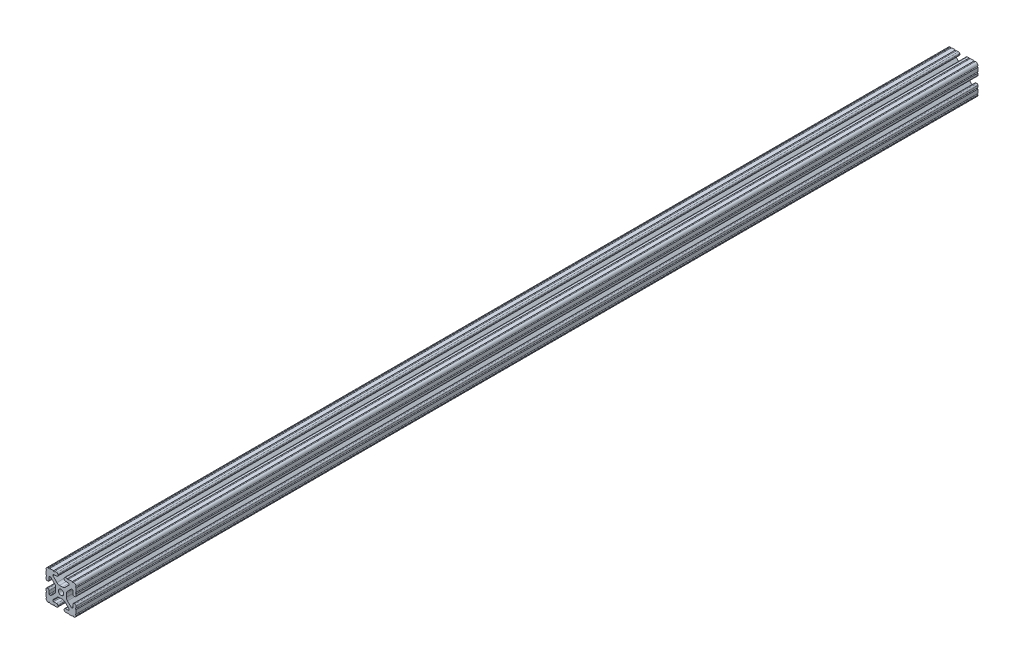
SolidWorks part; units mm, degrees
material "6061 Alloy"
ref_plane "Front Plane" through (0, 0, 0) normal (0, 0, 1) x (1, 0, 0)
ref_plane "Top Plane" through (0, 0, 0) normal (0, 1, 0) x (1, 0, 0)
ref_plane "Right Plane" through (0, 0, 0) normal (1, 0, 0) x (0, 0, -1)
sketch "Sketch1" plane through (0, 0, 0) normal (0, 0, 1) x (1, 0, 0)
  line L0 (0, 25.6181) -> (0, -24.623) construction
  line L1 (-20.8943, 0) -> (20.4607, 0) construction
  line L2 (-10.0229, 12.9148) -> (-5.2522, 8.144)
  line L3 (-10.287, 14.0843) -> (-10.287, 13.5524)
  line L4 (-5.6176, 14.986) -> (-9.3853, 14.986)
  line L5 (-4.064, 17.4964) -> (-4.064, 16.5396)
  line L6 (-7.9742, 19.05) -> (-5.6176, 19.05)
  line L7 (-14.3277, 19.05) -> (-9.4982, 19.05)
  line L8 (-19.05, 9.4961) -> (-19.05, 14.3277)
  line L9 (-19.05, 5.6176) -> (-19.05, 7.9763)
  line L10 (-16.5396, 4.064) -> (-17.4964, 4.064)
  line L11 (-14.986, 9.3853) -> (-14.986, 5.6176)
  line L12 (-13.516, 10.287) -> (-14.0843, 10.287)
  line L13 (-8.1476, 5.2921) -> (-12.8784, 10.0229)
  line L14 (-6.7564, -1.9335) -> (-6.7564, 1.9335)
  line L15 (-12.8784, -10.0229) -> (-8.1476, -5.2921)
  line L16 (-14.0843, -10.287) -> (-13.516, -10.287)
  line L17 (-14.986, -5.6176) -> (-14.986, -9.3853)
  line L18 (-17.4964, -4.064) -> (-16.5396, -4.064)
  line L19 (-19.05, -7.9763) -> (-19.05, -5.6176)
  line L20 (-19.05, -14.3277) -> (-19.05, -9.4961)
  line L21 (-9.4961, -19.05) -> (-14.3277, -19.05)
  line L22 (-5.6176, -19.05) -> (-7.9763, -19.05)
  line L23 (-4.064, -17.4964) -> (-4.064, -16.5396)
  line L24 (10.0229, -12.9148) -> (5.2522, -8.144)
  line L25 (10.287, -14.0843) -> (10.287, -13.5524)
  line L26 (5.6176, -14.986) -> (9.3853, -14.986)
  line L28 (-1.9022, 6.7564) -> (1.9022, 6.7564)
  line L29 (-1.9022, -6.7564) -> (1.9022, -6.7564)
  line L31 (-5.6176, -14.986) -> (-9.3853, -14.986)
  line L32 (-10.287, -14.0843) -> (-10.287, -13.5524)
  line L33 (-10.0229, -12.9148) -> (-5.2522, -8.144)
  line L66 (4.064, -16.5396) -> (4.064, -17.4964)
  line L67 (5.6176, -19.05) -> (7.9763, -19.05)
  line L68 (9.4961, -19.05) -> (14.3277, -19.05)
  line L69 (19.05, -14.3277) -> (19.05, -9.4961)
  line L70 (19.05, -7.9763) -> (19.05, -5.6176)
  line L71 (17.4964, -4.064) -> (16.5396, -4.064)
  line L72 (14.986, -5.6176) -> (14.986, -9.3853)
  line L73 (14.0843, -10.287) -> (13.516, -10.287)
  line L74 (12.8784, -10.0229) -> (8.1476, -5.2921)
  line L75 (6.7564, -1.9335) -> (6.7564, 1.9335)
  line L76 (8.1476, 5.2921) -> (12.8784, 10.0229)
  line L77 (13.516, 10.287) -> (14.0843, 10.287)
  line L78 (14.986, 9.3853) -> (14.986, 5.6176)
  line L79 (16.5396, 4.064) -> (17.4964, 4.064)
  line L80 (19.05, 5.6176) -> (19.05, 7.9763)
  line L81 (19.05, 9.4961) -> (19.05, 14.3277)
  line L82 (14.3277, 19.05) -> (9.4982, 19.05)
  line L83 (7.9742, 19.05) -> (5.6176, 19.05)
  line L84 (4.064, 17.4964) -> (4.064, 16.5396)
  line L85 (5.6176, 14.986) -> (9.3853, 14.986)
  line L86 (10.287, 14.0843) -> (10.287, 13.5524)
  line L87 (10.0229, 12.9148) -> (5.2522, 8.144)
  arc A0 (-10.0229, 12.9148) -> (-10.287, 13.5524) centre (-9.3853, 13.5524) cw
  circle A1 centre (0, 0) radius 3.3274
  arc A2 (-10.287, 14.0843) -> (-9.3853, 14.986) centre (-9.3853, 14.0843) cw
  arc A3 (-4.064, 16.5396) -> (-5.6176, 14.986) centre (-5.6176, 16.5396) cw
  arc A4 (-5.6176, 19.05) -> (-4.064, 17.4964) centre (-5.6176, 17.4964) cw
  arc A5 (-7.9742, 19.05) -> (-9.4982, 19.05) centre (-8.7362, 19.05) cw
  arc A6 (-14.3277, 19.05) -> (-15.8475, 19.05) centre (-15.0876, 18.9933) cw
  arc A7 (-19.05, 15.8475) -> (-15.8475, 19.05) centre (-15.8751, 15.8751) cw
  arc A8 (-19.05, 15.8475) -> (-19.05, 14.3277) centre (-18.9933, 15.0876) cw
  arc A9 (-19.05, 9.4961) -> (-19.05, 7.9763) centre (-18.9933, 8.7362) cw
  arc A10 (-17.4964, 4.064) -> (-19.05, 5.6176) centre (-17.4964, 5.6176) cw
  arc A11 (-14.986, 5.6176) -> (-16.5396, 4.064) centre (-16.5396, 5.6176) cw
  arc A12 (-14.986, 9.3853) -> (-14.0843, 10.287) centre (-14.0843, 9.3853) cw
  arc A13 (-13.516, 10.287) -> (-12.8784, 10.0229) centre (-13.516, 9.3853) cw
  arc A14 (-8.1476, 5.2921) -> (-6.7564, 1.9335) centre (-11.5062, 1.9335) cw
  arc A15 (-6.7564, -1.9335) -> (-8.1476, -5.2921) centre (-11.5062, -1.9335) cw
  arc A16 (-12.8784, -10.0229) -> (-13.516, -10.287) centre (-13.516, -9.3853) cw
  arc A17 (-14.0843, -10.287) -> (-14.986, -9.3853) centre (-14.0843, -9.3853) cw
  arc A18 (-16.5396, -4.064) -> (-14.986, -5.6176) centre (-16.5396, -5.6176) cw
  arc A19 (-19.05, -5.6176) -> (-17.4964, -4.064) centre (-17.4964, -5.6176) cw
  arc A20 (-19.05, -7.9763) -> (-19.05, -9.4961) centre (-18.9933, -8.7362) cw
  arc A21 (-19.05, -14.3277) -> (-19.05, -15.8475) centre (-18.9933, -15.0876) cw
  arc A22 (-15.8475, -19.05) -> (-19.05, -15.8475) centre (-15.8751, -15.8751) cw
  arc A23 (-15.8475, -19.05) -> (-14.3277, -19.05) centre (-15.0876, -18.9933) cw
  arc A24 (-9.4961, -19.05) -> (-7.9763, -19.05) centre (-8.7362, -18.9933) cw
  arc A25 (-4.064, -17.4964) -> (-5.6176, -19.05) centre (-5.6176, -17.4964) cw
  arc A26 (-5.2522, -8.144) -> (-1.9022, -6.7564) centre (-1.9022, -11.494) cw
  arc A27 (1.9022, -6.7564) -> (5.2522, -8.144) centre (1.9022, -11.494) cw
  arc A28 (10.0229, -12.9148) -> (10.287, -13.5524) centre (9.3853, -13.5524) cw
  arc A29 (10.287, -14.0843) -> (9.3853, -14.986) centre (9.3853, -14.0843) cw
  arc A30 (4.064, -16.5396) -> (5.6176, -14.986) centre (5.6176, -16.5396) cw
  arc A31 (-4.064, -16.5396) -> (-5.6176, -14.986) centre (-5.6176, -16.5396) ccw
  arc A32 (-10.287, -14.0843) -> (-9.3853, -14.986) centre (-9.3853, -14.0843) ccw
  arc A33 (-10.0229, -12.9148) -> (-10.287, -13.5524) centre (-9.3853, -13.5524) ccw
  arc A79 (4.064, -17.4964) -> (5.6176, -19.05) centre (5.6176, -17.4964) ccw
  arc A80 (9.4961, -19.05) -> (7.9763, -19.05) centre (8.7362, -18.9933) ccw
  arc A81 (15.8475, -19.05) -> (14.3277, -19.05) centre (15.0876, -18.9933) ccw
  arc A82 (15.8475, -19.05) -> (19.05, -15.8475) centre (15.8751, -15.8751) ccw
  arc A83 (19.05, -14.3277) -> (19.05, -15.8475) centre (18.9933, -15.0876) ccw
  arc A84 (19.05, -7.9763) -> (19.05, -9.4961) centre (18.9933, -8.7362) ccw
  arc A85 (19.05, -5.6176) -> (17.4964, -4.064) centre (17.4964, -5.6176) ccw
  arc A86 (16.5396, -4.064) -> (14.986, -5.6176) centre (16.5396, -5.6176) ccw
  arc A87 (14.0843, -10.287) -> (14.986, -9.3853) centre (14.0843, -9.3853) ccw
  arc A88 (12.8784, -10.0229) -> (13.516, -10.287) centre (13.516, -9.3853) ccw
  arc A89 (6.7564, -1.9335) -> (8.1476, -5.2921) centre (11.5062, -1.9335) ccw
  arc A90 (8.1476, 5.2921) -> (6.7564, 1.9335) centre (11.5062, 1.9335) ccw
  arc A91 (13.516, 10.287) -> (12.8784, 10.0229) centre (13.516, 9.3853) ccw
  arc A92 (14.986, 9.3853) -> (14.0843, 10.287) centre (14.0843, 9.3853) ccw
  arc A93 (14.986, 5.6176) -> (16.5396, 4.064) centre (16.5396, 5.6176) ccw
  arc A94 (17.4964, 4.064) -> (19.05, 5.6176) centre (17.4964, 5.6176) ccw
  arc A95 (19.05, 9.4961) -> (19.05, 7.9763) centre (18.9933, 8.7362) ccw
  arc A96 (19.05, 15.8475) -> (19.05, 14.3277) centre (18.9933, 15.0876) ccw
  arc A97 (19.05, 15.8475) -> (15.8475, 19.05) centre (15.8751, 15.8751) ccw
  arc A98 (14.3277, 19.05) -> (15.8475, 19.05) centre (15.0876, 18.9933) ccw
  arc A99 (7.9742, 19.05) -> (9.4982, 19.05) centre (8.7362, 19.05) ccw
  arc A100 (5.6176, 19.05) -> (4.064, 17.4964) centre (5.6176, 17.4964) ccw
  arc A101 (4.064, 16.5396) -> (5.6176, 14.986) centre (5.6176, 16.5396) ccw
  arc A102 (10.287, 14.0843) -> (9.3853, 14.986) centre (9.3853, 14.0843) ccw
  arc A103 (10.0229, 12.9148) -> (10.287, 13.5524) centre (9.3853, 13.5524) ccw
  arc A104 (1.9022, 6.7564) -> (5.2522, 8.144) centre (1.9022, 11.494) ccw
  arc A105 (-5.2522, 8.144) -> (-1.9022, 6.7564) centre (-1.9022, 11.494) ccw
  dimension "D1" = 6.6548
  dimension "D2" = 19.05
  dimension "D3" = 38.1
  dimension "D4" = 20.574
  dimension "D5" = 13.5128
  dimension "D6" = 4.064
  dimension "D7" = 8.128
  dimension "D8" = 4.064
  dimension "D9" = 12.2936
extrude "Extrude1" add sketch "Sketch1" against normal blind 1143
